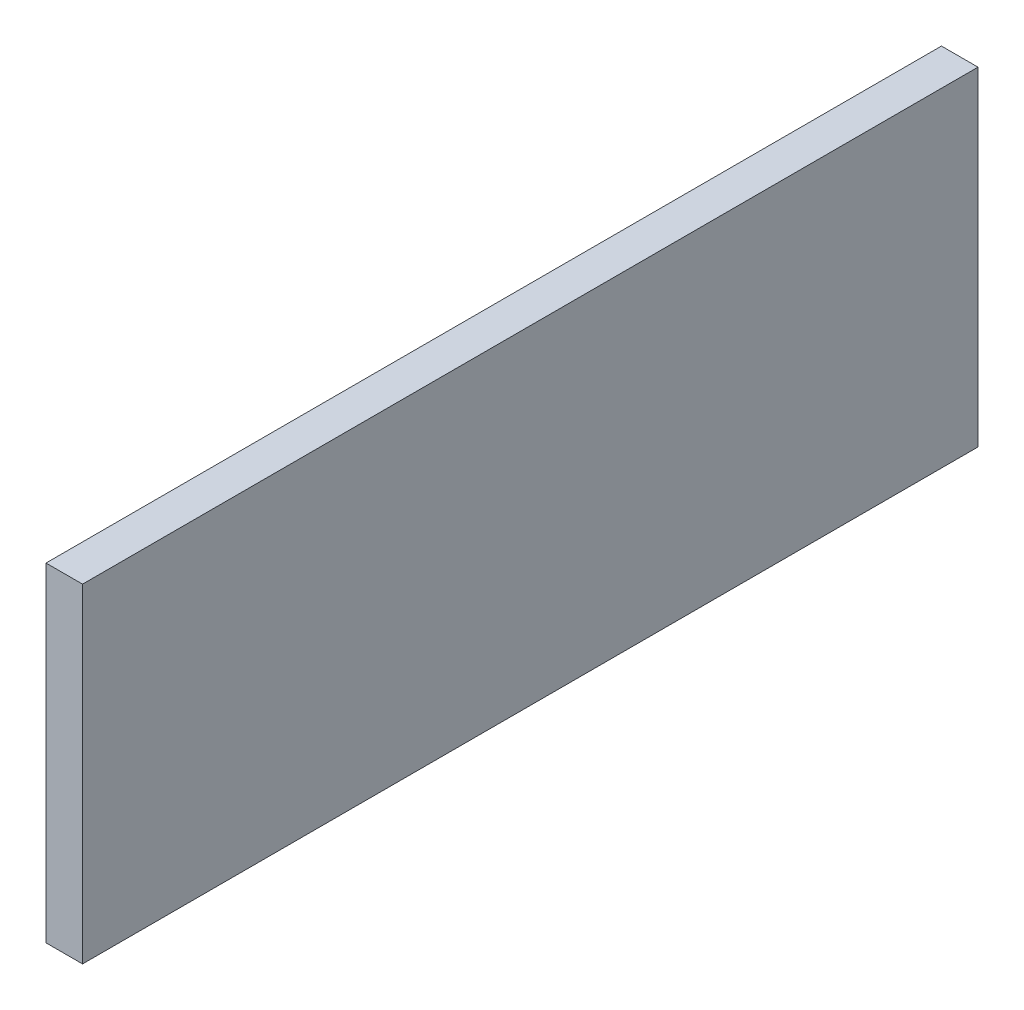
SolidWorks part; units mm, degrees
ref_plane "Front Plane" through (0, 0, 0) normal (0, 0, 1) x (1, 0, 0)
ref_plane "Top Plane" through (0, 0, 0) normal (0, 1, 0) x (1, 0, 0)
ref_plane "Right Plane" through (0, 0, 0) normal (1, 0, 0) x (0, 0, -1)
sketch "Sketch1" plane through (0, 0, 0) normal (1, 0, 0) x (0, 0, -1)
  line L1 (0, 0) -> (311.15, 0)
  line L2 (0, 0) -> (0, 114.3)
  line L3 (0, 114.3) -> (311.15, 114.3)
  line L4 (311.15, 0) -> (311.15, 114.3)
  dimension "D1" = 114.3
  dimension "D2" = 311.15
extrude "Boss-Extrude1" add sketch "Sketch1" along normal blind 12.7
